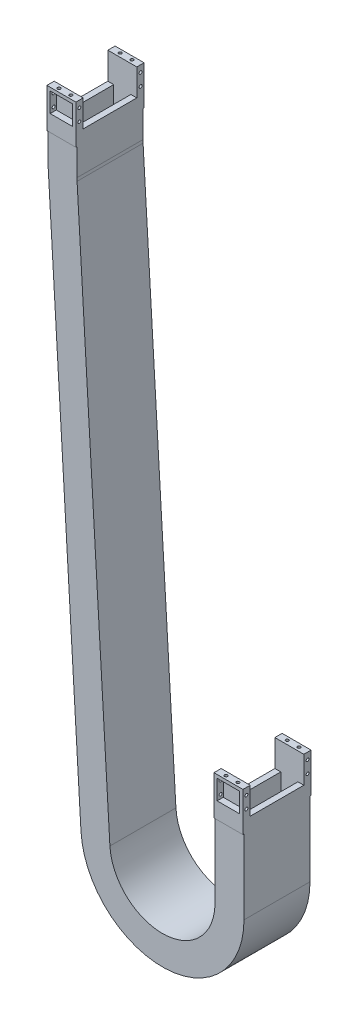
SolidWorks part; units mm, degrees
material "ABS"
ref_plane "Front Plane" through (0, 0, 0) normal (0, 0, 1) x (1, 0, 0)
ref_plane "Top Plane" through (0, 0, 0) normal (0, 1, 0) x (1, 0, 0)
ref_plane "Right Plane" through (0, 0, 0) normal (1, 0, 0) x (0, 0, -1)
ref_plane "Plane1" through (0, 300, 0) normal (0, 1, 0) x (-1, 0, 0)
sketch "Sketch1" plane through (0, 0, 0) normal (0, 0, 1) x (1, 0, 0)
  line L0 (-311.2, 954.5) -> (-311.2, 904.5)
  line L1 (0, -137.5026) -> (0, 0)
  line L2 (164.2548, 1105.5) -> (-1434.5794, 1105.5) construction
  line L3 (-249.785, -144.8316) -> (-310.985, 897.171)
  line L4 (164.2548, 1105.5) -> (164.2548, 1309.072) construction
  line L5 (164.2548, 1309.072) -> (-1459.7452, 1309.072) construction
  line L6 (164.2548, 1309.072) -> (164.2548, 1525.2437) construction
  line L7 (164.2548, 1525.2437) -> (-1067.0461, 1525.2437) construction
  line L8 (164.2548, 1309.072) -> (193.2548, 1309.072) construction
  line L9 (164.2548, 1525.2437) -> (164.2548, 1677.4286) construction
  line L10 (164.2548, 1677.4286) -> (26.7522, 1677.4286) construction
  line L11 (164.2548, 1677.4286) -> (164.2548, 1767.1262) construction
  line L12 (164.2548, 1767.1262) -> (103.0548, 1767.1262) construction
  line L13 (164.2548, 1767.1262) -> (164.2548, 1879.3796) construction
  line L14 (164.2548, 1879.3796) -> (-1921.5461, 1879.3796) construction
  arc A0 (-311.2, 904.5) -> (-310.985, 897.171) centre (-186.2, 904.5) ccw
  arc A1 (-249.785, -144.8316) -> (0, -137.5026) centre (-125, -137.5026) ccw
  point P2 (-310.2, 1104.5)
  dimension "D4" = 150
  dimension "D1" = 1105.5
  dimension "D13" = 1231.3009
  dimension "D6" = 125
  dimension "D2" = 310.2
  dimension "D3" = 1
  dimension "D5" = 1
  dimension "D7" = 137.5026
  dimension "D8" = 50
  dimension "D9" = 1043.7983
  dimension "D10" = 1598.8342
  dimension "D11" = 1624
  dimension "D12" = 29
  dimension "D14" = 137.5026
  dimension "D15" = 61.2
  dimension "D16" = 2085.8009
sketch "Sketch13" plane through (0, 0, 0) normal (0, 0, 1) x (1, 0, 0)
  line L0 (0, 228.6) -> (0, 203.2)
  line L1 (0, 228.6) -> (100, 228.6)
  line L2 (0, 203.2) -> (32, 203.2)
  line L3 (0, 177.8) -> (56, 177.8)
  line L4 (0, 152.4) -> (125, 152.4)
  line L5 (0, 127) -> (1, 127)
  line L6 (0, 101.6) -> (310.2, 101.6)
  line L7 (0, 76.2) -> (1105.5, 76.2)
  line L8 (0, 50.8) -> (1, 50.8)
  line L9 (0, 25.4) -> (1145, 25.4)
  line L10 (0, 203.2) -> (0, 177.8)
  line L11 (0, 177.8) -> (0, 152.4)
  line L12 (0, 152.4) -> (0, 127)
  line L13 (0, 127) -> (0, 101.6)
  line L14 (0, 101.6) -> (0, 76.2)
  line L15 (0, 76.2) -> (0, 50.8)
  line L16 (0, 50.8) -> (0, 25.4)
  line L17 (0, 25.4) -> (0, 0)
  line L18 (0, 228.6) -> (0, 254)
  line L19 (0, 254) -> (50, 254)
  line L20 (0, 254) -> (0, 279.4)
  line L21 (0, 279.4) -> (3, 279.4)
  dimension "D1" = 25.4
  dimension "D2" = 1145
  dimension "D3" = 1
  dimension "D4" = 1105.5
  dimension "D5" = 310.2
  dimension "D6" = 1
  dimension "D7" = 125
  dimension "D8" = 56
  dimension "D9" = 32
  dimension "D10" = 100
  dimension "D11" = 50
  dimension "D12" = 3
sketch "Sketch2" plane through (0, 0, 0) normal (0, 1, 0) x (1, 0, 0)
  line L0 (0, -11.5) -> (0, 0) construction
  line L1 (-27, 0) -> (27, 0)
  line L2 (-27, 0) -> (-27, -123)
  line L3 (-27, -123) -> (27, -123)
  line L4 (27, 0) -> (27, -123)
  line L5 (-16, -11.5) -> (16, -11.5)
  line L6 (-16, -11.5) -> (-16, -111.5)
  line L7 (-16, -111.5) -> (16, -111.5)
  line L8 (16, -11.5) -> (16, -111.5)
  line L9 (-27, -61.5) -> (-16, -61.5) construction
  dimension "D1" = 54
  dimension "D2" = 11.5
  dimension "D3" = 32
  dimension "D4" = 100
sweep "Sweep1" add profiles "Sketch2" path "Sketch1"
sketch "Sketch12" plane through (0, 0, 0) normal (0, 1, 0) x (1, 0, 0)
  line L0 (16, -11.5) -> (-16, -11.5) construction
  line L1 (-16, -11.5) -> (-16, -111.5) construction
  line L2 (16, -111.5) -> (16, -11.5) construction
  line L3 (-16, -111.5) -> (16, -111.5) construction
  line L4 (-27, 0) -> (-27, -123)
  line L5 (-27, -123) -> (27, -123)
  line L6 (27, -123) -> (27, 0)
  line L7 (27, 0) -> (-27, 0)
  line L8 (-27, 0) -> (-27, -123)
  line L9 (-27, -123) -> (27, -123)
  line L10 (27, -123) -> (27, 0)
  line L11 (27, 0) -> (-27, 0)
  line L12 (16, -11.5) -> (-16, -11.5)
  line L13 (-16, -11.5) -> (-16, -111.5)
  line L14 (16, -111.5) -> (16, -11.5)
  line L15 (-16, -111.5) -> (16, -111.5)
  dimension "D1" = 0
extrude "Boss-Extrude1" add sketch "Sketch12" along normal blind 1
sketch "Sketch3" plane through (0, 1, 0) normal (0, 1, 0) x (1, 0, 0)
  line L0 (27, -123) -> (27, 0) construction
  line L1 (-27, -125) -> (27, -125)
  line L2 (-27, -125) -> (-27, 2)
  line L3 (-27, 2) -> (27, 2)
  line L4 (27, -125) -> (27, 2)
  line L5 (-27, 0) -> (-27, -123) construction
  line L6 (-16, -61.5) -> (27, -61.5) construction
  line L7 (-16, -11.5) -> (-16, -111.5) construction
  line L9 (16, -11.5) -> (-16, -11.5) construction
  line L12 (16, -11.5) -> (-16, -11.5)
  line L13 (16, -111.5) -> (16, -11.5)
  line L14 (-16, -11.5) -> (-16, -111.5)
  line L15 (-16, -111.5) -> (16, -111.5)
  dimension "D1" = 13.5
extrude "Extrude1" add sketch "Sketch3" along normal blind 73
sketch "Sketch4" plane through (27, 0, 0) normal (1, 0, 0) x (0, 0, -1)
  line L0 (2, 74) -> (-125, 74) construction
  line L1 (-111.5, 74) -> (-11.5, 74)
  line L2 (-111.5, 74) -> (-111.5, 24)
  line L3 (-111.5, 24) -> (-11.5, 24)
  line L4 (-11.5, 74) -> (-11.5, 24)
  line L5 (-11.5, -137.5026) -> (-11.5, 74) construction
  line L6 (-111.5, -137.5026) -> (-111.5, 74) construction
  line L7 (-61.5, 61.5) -> (-61.5, 74) construction
  line L8 (-118.5, 61.5) -> (-4.5, 61.5) construction
  line L9 (-118.5, 61.5) -> (-118.5, 39) construction
  line L10 (-118.5, 39) -> (-4.5, 39) construction
  line L11 (-4.5, 61.5) -> (-4.5, 39) construction
  circle A0 centre (-118.5, 61.5) radius 2.75
  circle A1 centre (-118.5, 39) radius 2.75
  circle A2 centre (-4.5, 39) radius 2.75
  circle A3 centre (-4.5, 61.5) radius 2.75
  dimension "D2" = 5.5
  dimension "D1" = 50
  dimension "D3" = 14
  dimension "D4" = 12.5
  dimension "D5" = 22.5
extrude "Extrude2" cut sketch "Sketch4" against normal up to surface (54 mm away)
sketch "Sketch7" plane through (0, 954.5, 0) normal (0, 1, 0) x (1, 0, 0)
  line L1 (-338.2, -125) -> (-284.2, -125)
  line L2 (-338.2, -125) -> (-338.2, 2)
  line L3 (-338.2, 2) -> (-284.2, 2)
  line L4 (-284.2, -125) -> (-284.2, 2)
  line L8 (-295.2, -11.5) -> (-327.2, -11.5)
  line L9 (-327.2, -11.5) -> (-327.2, -111.5)
  line L10 (-327.2, -111.5) -> (-295.2, -111.5)
  line L11 (-295.2, -111.5) -> (-295.2, -11.5)
  line L12 (-295.2, -61.5) -> (-284.2, -61.5) construction
  line L15 (-284.2, 0) -> (-284.2, -123) construction
  line L16 (-338.2, -123) -> (-338.2, 0) construction
  dimension "D1" = 13.5
extrude "Extrude5" add sketch "Sketch7" along normal blind 73
sketch "Sketch8" plane through (-284.2, 0, 0) normal (1, 0, 0) x (0, 0, -1)
  line L0 (2, 1027.5) -> (-125, 1027.5) construction
  line L1 (-111.5, 1027.5) -> (-11.5, 1027.5)
  line L2 (-111.5, 1027.5) -> (-111.5, 977.5)
  line L3 (-111.5, 977.5) -> (-11.5, 977.5)
  line L4 (-11.5, 1027.5) -> (-11.5, 977.5)
  line L5 (-61.5, 1015) -> (-61.5, 1027.5) construction
  line L6 (-118.5, 992.5) -> (-4.5, 992.5) construction
  line L7 (-118.5, 992.5) -> (-118.5, 1015) construction
  line L8 (-118.5, 1015) -> (-4.5, 1015) construction
  line L9 (-4.5, 992.5) -> (-4.5, 1015) construction
  line L10 (-111.5, 904.5) -> (-111.5, 1027.5) construction
  line L11 (-11.5, 904.5) -> (-11.5, 1027.5) construction
  circle A0 centre (-4.5, 992.5) radius 2.75
  circle A1 centre (-4.5, 1015) radius 2.75
  circle A2 centre (-118.5, 992.5) radius 2.75
  circle A3 centre (-118.5, 1015) radius 2.75
  dimension "D5" = 5.5
  dimension "D1" = 7
  dimension "D2" = 12.5
  dimension "D3" = 22.5
  dimension "D4" = 50
extrude "Extrude6" cut sketch "Sketch8" against normal up to surface (54 mm away) up to face at (-338.2, 954, 61.25)
sketch "Sketch5" plane through (0, 0, 125) normal (0, 0, 1) x (1, 0, 0)
  line L1 (21, 68) -> (-21, 68)
  line L2 (21, 68) -> (21, 31.5)
  line L3 (21, 31.5) -> (-21, 31.5)
  line L4 (-21, 68) -> (-21, 31.5)
  line L6 (27, 74) -> (-27, 74) construction
  line L7 (-338.2, 1027.5) -> (-338.2, 954.5) construction
  line L8 (-332.2, 1021.5) -> (-290.2, 1021.5)
  line L9 (-332.2, 1021.5) -> (-332.2, 985)
  line L10 (-332.2, 985) -> (-290.2, 985)
  line L11 (-290.2, 1021.5) -> (-290.2, 985)
  line L12 (-284.2, 1027.5) -> (-284.2, 954.5) construction
  line L13 (-284.2, 1027.5) -> (-338.2, 1027.5) construction
  line L14 (27, 74) -> (27, 1) construction
  line L15 (-27, 74) -> (-27, 1) construction
  dimension "D1" = 6
  dimension "D2" = 6
  dimension "D3" = 6
  dimension "D4" = 42.5
  dimension "D5" = 6
  dimension "D6" = 6
  dimension "D7" = 6
  dimension "D8" = 42.5
extrude "Extrude3" cut sketch "Sketch5" against normal blind 11.5
sketch "Sketch6" plane through (0, 0, -2) normal (0, 0, -1) x (-1, 0, 0)
  line L4 (-21, 68) -> (-21, 31.5)
  line L5 (-21, 31.5) -> (21, 31.5)
  line L6 (-21, 68) -> (-21, 31.5)
  line L7 (21, 68) -> (-21, 68)
  line L8 (21, 31.5) -> (21, 68)
  line L9 (-21, 31.5) -> (21, 31.5)
  line L10 (21, 31.5) -> (21, 68)
  line L11 (21, 68) -> (-21, 68)
  line L12 (332.2, 985) -> (332.2, 1021.5)
  line L13 (290.2, 985) -> (332.2, 985)
  line L14 (290.2, 1021.5) -> (290.2, 985)
  line L15 (332.2, 1021.5) -> (290.2, 1021.5)
  line L16 (332.2, 985) -> (332.2, 1021.5)
  line L17 (290.2, 985) -> (332.2, 985)
  line L18 (290.2, 1021.5) -> (290.2, 985)
  line L19 (332.2, 1021.5) -> (290.2, 1021.5)
  dimension "D1" = 0
  dimension "D2" = 0
extrude "Extrude4" cut sketch "Sketch6" against normal blind 11.5
sketch "Sketch9" plane through (0, 74, 0) normal (0, 1, 0) x (1, 0, 0)
  line L0 (27, -111.5) -> (-27, -111.5) construction
  line L1 (-11, -118.5) -> (11, -118.5) construction
  line L2 (-11, -118.5) -> (-11, -4.5) construction
  line L3 (-11, -4.5) -> (11, -4.5) construction
  line L4 (11, -118.5) -> (11, -4.5) construction
  line L5 (-27, -11.5) -> (-27, -111.5) construction
  line L6 (-27, -11.5) -> (-27, -111.5) construction
  line L7 (27, -111.5) -> (-27, -111.5) construction
  line L8 (0, -118.5) -> (0, -111.5) construction
  line L9 (11, -61.5) -> (-27, -61.5) construction
  circle A0 centre (-11, -118.5) radius 2.75
  circle A1 centre (11, -118.5) radius 2.75
  circle A2 centre (11, -4.5) radius 2.75
  circle A3 centre (-11, -4.5) radius 2.75
  dimension "D1" = 5.5
  dimension "D2" = 22
  dimension "D3" = 7
extrude "Extrude7" cut sketch "Sketch9" against normal blind 7
sketch "Sketch10" plane through (0, 1027.5, 0) normal (0, 1, 0) x (1, 0, 0)
  line L0 (-284.2, -111.5) -> (-338.2, -111.5) construction
  line L1 (-322.2, -118.5) -> (-300.2, -118.5) construction
  line L2 (-322.2, -118.5) -> (-322.2, -4.5) construction
  line L3 (-322.2, -4.5) -> (-300.2, -4.5) construction
  line L4 (-300.2, -118.5) -> (-300.2, -4.5) construction
  line L5 (-338.2, -11.5) -> (-338.2, -111.5) construction
  line L6 (-284.2, -111.5) -> (-338.2, -111.5) construction
  line L7 (-338.2, -11.5) -> (-338.2, -111.5) construction
  line L8 (-311.2, -111.5) -> (-311.2, -118.5) construction
  line L9 (-338.2, -61.5) -> (-300.2, -61.5) construction
  circle A0 centre (-322.2, -118.5) radius 2.75
  circle A1 centre (-300.2, -118.5) radius 2.75
  circle A2 centre (-322.2, -4.5) radius 2.75
  circle A3 centre (-300.2, -4.5) radius 2.75
  dimension "D1" = 5.5
  dimension "D2" = 22
  dimension "D3" = 7
extrude "Extrude8" cut sketch "Sketch10" against normal blind 7
other "Freeze***"
